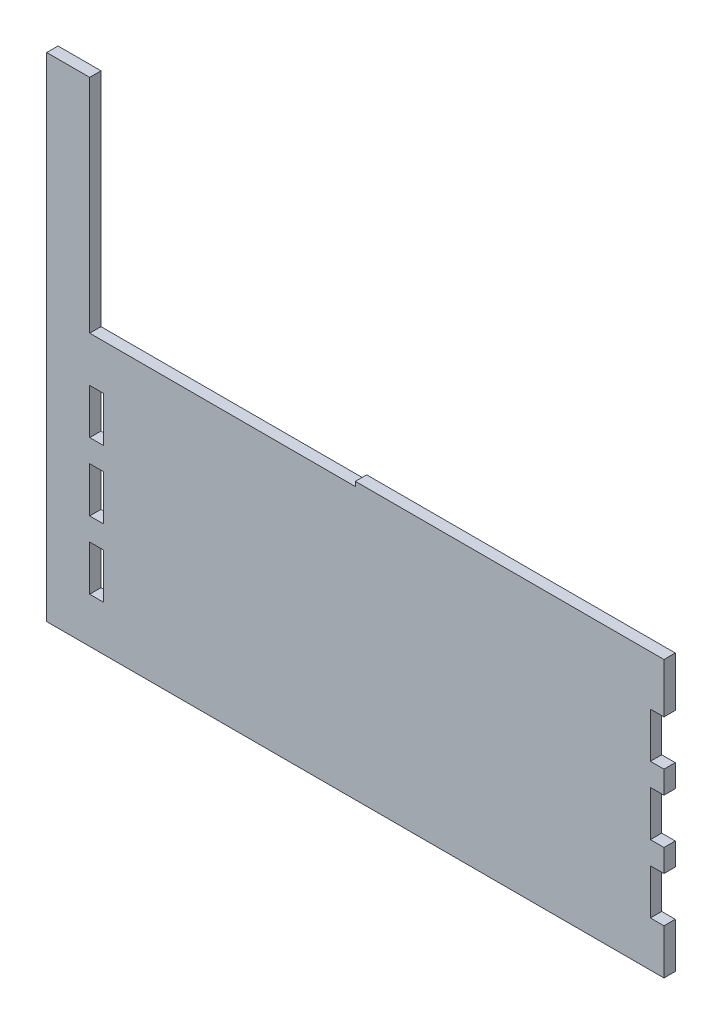
SolidWorks part; units mm, degrees
ref_plane "Front Plane" through (0, 0, 0) normal (0, 0, 1) x (1, 0, 0)
ref_plane "Top Plane" through (0, 0, 0) normal (0, 1, 0) x (1, 0, 0)
ref_plane "Right Plane" through (0, 0, 0) normal (1, 0, 0) x (0, 0, -1)
sketch "Sketch1" plane through (0, 0, 0) normal (0, 0, 1) x (1, 0, 0)
  line L1 (-136.5, -61) -> (136.5, -61)
  line L2 (-136.5, -61) -> (-136.5, 61)
  line L3 (-136.5, 61) -> (136.5, 61)
  line L4 (136.5, -61) -> (136.5, 61)
  line L5 (0, 61) -> (0, -61) construction
  line L6 (-136.5, 0) -> (136.5, 0) construction
  point P0 (0, 0)
  dimension "D1" = 273
  dimension "D2" = 122
extrude "Boss-Extrude1" add sketch "Sketch1" along normal blind 5
sketch "Sketch2" plane through (0, 0, 5) normal (0, 0, 1) x (1, 0, 0)
  line L1 (-136.5, 61) -> (-117.5, 61)
  line L2 (-136.5, 61) -> (-136.5, 157)
  line L3 (-136.5, 157) -> (-117.5, 157)
  line L4 (-117.5, 61) -> (-117.5, 157)
  dimension "D1" = 96
  dimension "D2" = 19
extrude "Boss-Extrude2" add sketch "Sketch2" against normal blind 5
sketch "Sketch3" plane through (0, 0, 5) normal (0, 0, 1) x (1, 0, 0)
  line L1 (-117.5, 61) -> (136.5, 61)
  line L2 (-117.5, 61) -> (-117.5, -61)
  line L3 (-117.5, -61) -> (136.5, -61)
  line L4 (136.5, 61) -> (136.5, -61)
  line L5 (130.5, 39) -> (142.5, 39)
  line L6 (130.5, 39) -> (130.5, 19)
  line L7 (130.5, 19) -> (142.5, 19)
  line L8 (142.5, 39) -> (142.5, 19)
  line L9 (136.5, 19) -> (136.5, 39) construction
  line L10 (130.5, 29) -> (142.5, 29) construction
  line L11 (130.5, -11) -> (142.5, -11)
  line L12 (130.5, -11) -> (130.5, 9)
  line L13 (130.5, 9) -> (142.5, 9)
  line L14 (142.5, -11) -> (142.5, 9)
  line L15 (136.5, 9) -> (136.5, -11) construction
  line L16 (130.5, -1) -> (142.5, -1) construction
  line L17 (130.5, -41) -> (142.5, -41)
  line L18 (130.5, -41) -> (130.5, -21)
  line L19 (130.5, -21) -> (142.5, -21)
  line L20 (142.5, -41) -> (142.5, -21)
  line L21 (136.5, -21) -> (136.5, -41) construction
  line L22 (130.5, -31) -> (142.5, -31) construction
  line L23 (-123.5, 39) -> (-111.5, 39)
  line L24 (-123.5, 39) -> (-123.5, 19)
  line L25 (-123.5, 19) -> (-111.5, 19)
  line L26 (-111.5, 39) -> (-111.5, 19)
  line L27 (-117.5, 19) -> (-117.5, 39) construction
  line L28 (-123.5, 29) -> (-111.5, 29) construction
  line L29 (-123.5, -11) -> (-111.5, -11)
  line L30 (-123.5, -11) -> (-123.5, 9)
  line L31 (-123.5, 9) -> (-111.5, 9)
  line L32 (-111.5, -11) -> (-111.5, 9)
  line L33 (-117.5, 9) -> (-117.5, -11) construction
  line L34 (-123.5, -1) -> (-111.5, -1) construction
  line L35 (-123.5, -41) -> (-111.5, -41)
  line L36 (-123.5, -41) -> (-123.5, -21)
  line L37 (-123.5, -21) -> (-111.5, -21)
  line L38 (-111.5, -41) -> (-111.5, -21)
  line L39 (-117.5, -21) -> (-117.5, -41) construction
  line L40 (-123.5, -31) -> (-111.5, -31) construction
  point P6 (136.5, 29)
  point P10 (136.5, -1)
  point P14 (136.5, -31)
  point P18 (-117.5, 29)
  point P22 (-117.5, -1)
  point P26 (-117.5, -31)
  dimension "D1" = 30
  dimension "D2" = 30
  dimension "D3" = 30
  dimension "D4" = 12
  dimension "D5" = 12
  dimension "D6" = 12
  dimension "D7" = 20
  dimension "D8" = 20
  dimension "D9" = 20
  dimension "D10" = 12
  dimension "D11" = 12
  dimension "D12" = 12
  dimension "D13" = 20
  dimension "D14" = 20
  dimension "D15" = 20
  dimension "D16" = 30
  dimension "D17" = 30
  dimension "D18" = 30
extrude "Cut-Extrude1" cut sketch "Sketch3" against normal blind 6 contours L26 L23 L2 L25 | L29 L32 L31 L2 | L35 L38 L37 L2 | L6 L7 L4 L5 | L13 L12 L11 L4 | L19 L18 L17 L4
sketch "Sketch6" plane through (0, 0, 5) normal (0, 0, 1) x (1, 0, 0)
  line L1 (-117.5, 61) -> (136.5, 61)
  line L2 (-117.5, 61) -> (-117.5, -61)
  line L3 (-117.5, -61) -> (136.5, -61)
  line L4 (136.5, 61) -> (136.5, -61)
  line L5 (-117.5, 61) -> (136.5, 61)
  line L6 (-117.5, 61) -> (-117.5, 59)
  line L7 (-117.5, 59) -> (136.5, 59)
  line L8 (136.5, 61) -> (136.5, 59)
  line L9 (-117.5, 61) -> (0, 61)
  line L10 (-117.5, 61) -> (-117.5, 59)
  line L11 (-117.5, 59) -> (0, 59)
  line L12 (0, 61) -> (0, 59)
  dimension "D1" = 2
extrude "Cut-Extrude3" cut sketch "Sketch6" against normal blind 6 contours L12 L5 L2 L7
